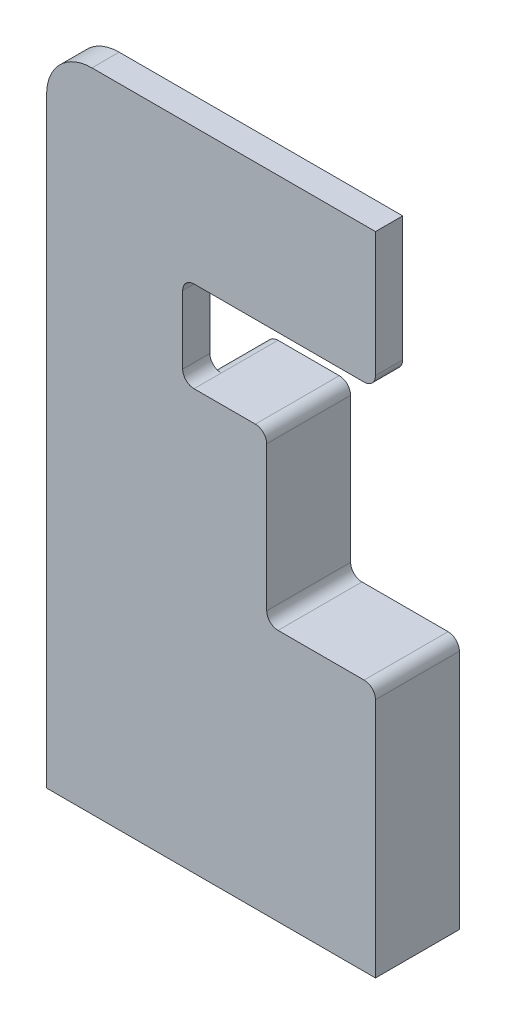
SolidWorks part; units mm, degrees
ref_plane "Front Plane" through (0, 0, 0) normal (0, 0, 1) x (1, 0, 0)
ref_plane "Top Plane" through (0, 0, 0) normal (0, 1, 0) x (1, 0, 0)
ref_plane "Right Plane" through (0, 0, 0) normal (1, 0, 0) x (0, 0, -1)
sketch "Sketch1" plane through (0, 0, 0) normal (0, 0, 1) x (1, 0, 0)
  line L1 (-8.5, 22.5) -> (8.5, 22.5)
  line L2 (-8.5, 22.5) -> (-8.5, -22.5)
  line L3 (-8.5, -22.5) -> (8.5, -22.5)
  line L4 (8.5, 22.5) -> (8.5, -22.5)
  line L5 (-8.5, 22.5) -> (8.5, -22.5) construction
  line L6 (-8.5, -22.5) -> (8.5, 22.5) construction
  point P0 (0, 0)
  dimension "D1" = 17
  dimension "D2" = 45
extrude "Boss-Extrude1" add sketch "Sketch1" along normal blind 12
sketch "Sketch2" plane through (0, 0, 12) normal (0, 0, 1) x (1, 0, 0)
  line L0 (-8.5, -22.5) -> (-8.5, 22.5)
  line L1 (-8.5, 22.5) -> (8.5, 22.5)
  line L2 (8.5, 22.5) -> (8.5, 34.5)
  line L3 (8.5, 34.5) -> (-20.5, 34.5)
  line L4 (-20.5, 34.5) -> (-20.5, -22.5)
  line L5 (-20.5, -22.5) -> (-8.5, -22.5)
  dimension "D1" = 12
  dimension "D2" = 12
extrude "Boss-Extrude2" add sketch "Sketch2" against normal blind 7
fillet "Fillet1" radius 4 1 edges at (-20.5, 34.5, 8.5)
sketch "Sketch3" plane through (0, 0, 0) normal (0, 0, -1) x (-1, 0, 0)
  line L1 (-2.5, -0.25) -> (1.0917, -0.25)
  line L3 (-8.5, 34.5) -> (16.5, 34.5) construction
  line L4 (-2.5, 34.5) -> (1.0917, 34.5)
  line L5 (1.0917, 22.5) -> (1.0917, -0.25)
  line L6 (1.0917, 22.5) -> (-8.5, 22.5)
  line L7 (-2.5, 34.5) -> (-3.5, 34.5)
  line L9 (-2.5, -0.25) -> (-3.5, -0.25)
  line L12 (-8.5, 22.5) -> (-8.5, -0.25)
  line L13 (-8.5, -22.5) -> (-8.5, 22.5) construction
  line L14 (-8.5, -0.25) -> (-3.5, -0.25)
  line L17 (-8.5, 22.5) -> (8.5, 22.5) construction
extrude "Cut-Extrude1" cut sketch "Sketch3" against normal through all
sketch "Sketch4" plane through (0, 0, 12) normal (0, 0, 1) x (1, 0, 0)
  line L0 (8.5, 34.5) -> (22.6833, 34.5)
  line L1 (8.5, 22.5) -> (8.5, -0.25)
  line L7 (-1.0917, 22.5) -> (8.5, 22.5)
  line L9 (8.5, -0.25) -> (-1.0917, -0.25)
  line L10 (8.5, 34.5) -> (-16.5, 34.5)
  line L11 (-20.5, 30.5) -> (-20.5, -22.5)
  line L12 (-20.5, -22.5) -> (8.5, -22.5)
  line L13 (8.5, -22.5) -> (8.5, -0.25)
  line L14 (-1.0917, -0.25) -> (-1.0917, 22.5)
  line L18 (8.5, 34.5) -> (-16.5, 34.5)
  line L19 (-20.5, 30.5) -> (-20.5, -22.5)
  line L20 (-20.5, -22.5) -> (8.5, -22.5)
  line L21 (8.5, -22.5) -> (8.5, -0.25)
  line L25 (8.5, 22.5) -> (8.5, 34.5)
  line L26 (8.5, 22.5) -> (8.5, 34.5)
  arc A1 (-16.5, 34.5) -> (-20.5, 30.5) centre (-16.5, 30.5) ccw
  arc A2 (-16.5, 34.5) -> (-20.5, 30.5) centre (-16.5, 30.5) ccw
  line M10 (8.5, -0.25) -> (-1.0917, -0.25)
  line M11 (-1.0917, -0.25) -> (-1.0917, 22.5)
  line M12 (8.5, 34.5) -> (-16.5, 34.5)
  arc M13 (-16.5, 34.5) -> (-20.5, 30.5) centre (-16.5, 30.5) ccw
  line M14 (-20.5, 30.5) -> (-20.5, -22.5)
  line M15 (-20.5, -22.5) -> (8.5, -22.5)
  line M16 (8.5, -22.5) -> (8.5, -0.25)
  line M20 (-1.0917, 22.5) -> (8.5, 22.5)
  line M31 (8.5, 22.5) -> (8.5, 34.5)
  dimension "D1" = 0
extrude "Cut-Extrude2" cut sketch "Sketch4" against normal offset from surface (4.6 mm away) 2.4 contours M11 M20 M31 M12 M13 M14 M15 M16 M10 up to face at (-7.4275, 15.3536, 5)
sketch "Sketch5" plane through (0, 0, 0) normal (0, 0, -1) x (-1, 0, 0)
  line L1 (8.5, 22.5) -> (0.5, 22.5)
  line L2 (8.5, 22.5) -> (8.5, 14.5)
  line L3 (8.5, 14.5) -> (0.5, 14.5)
  line L4 (0.5, 22.5) -> (0.5, 14.5)
  line M9 (8.5, -22.5) -> (8.5, 22.5)
  line M10 (8.5, 22.5) -> (1.0917, 22.5)
  dimension "D1" = 8
extrude "Cut-Extrude3" cut sketch "Sketch5" against normal through all contours L4 L3 M10 M9
fillet "Fillet2" radius 1 6 edges at (-8.5, 22.5, 6.2) (-8.5, 14.5, 6.2) (-1.0917, 14.5, 3.7) (-1.0917, -0.25, 3.7) (8.5, -0.25, 3.7) (8.5, 22.5, 6.2)
fillet "Fillet3" radius 1 2 edges at (-8.5, -22.5, 2.5) (-8.5, 14.5, 2.5)
